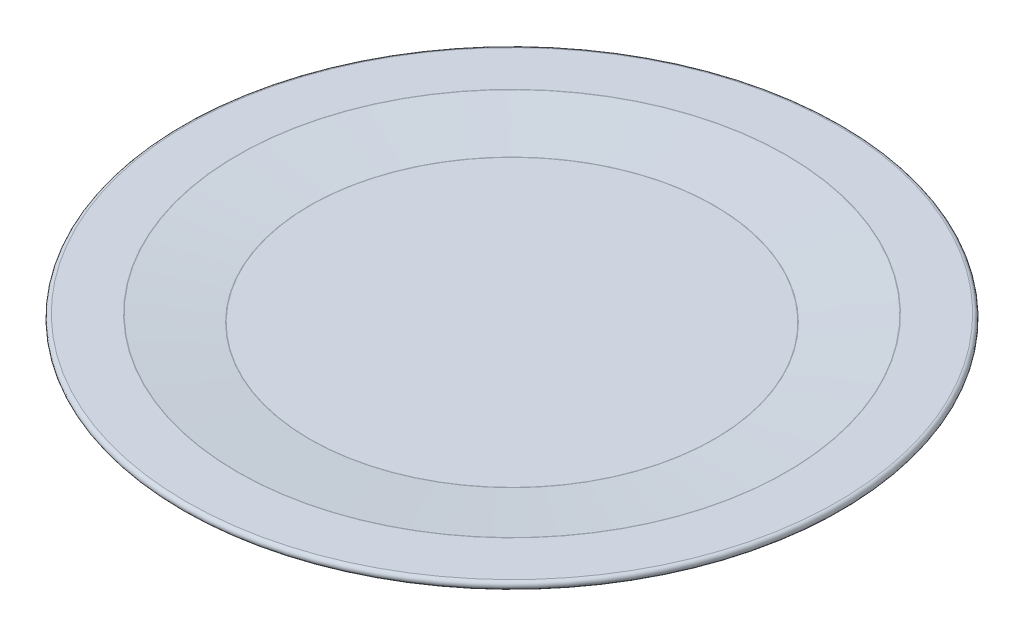
SolidWorks part; units mm, degrees
ref_plane "Front Plane" through (0, 0, 0) normal (0, 0, 1) x (1, 0, 0)
ref_plane "Top Plane" through (0, 0, 0) normal (0, 1, 0) x (1, 0, 0)
ref_plane "Right Plane" through (0, 0, 0) normal (1, 0, 0) x (0, 0, -1)
sketch "Sketch1" plane through (0, 0, 0) normal (0, 1, 0) x (1, 0, 0)
  circle A1 centre (0, 0) radius 203.2
extrude "Boss-Extrude1" add sketch "Sketch1" along normal blind 12.7 draft 64 draft outward yes
sketch "Sketch2" plane through (0, 12.7, 0) normal (0, 1, 0) x (1, 0, 0)
  circle A0 centre (0, 0) radius 183.8712
extrude "Cut-Extrude1" cut sketch "Sketch2" against normal blind 5.08 draft 84
fillet "Fillet1" radius 2.54 3 edges at (0, 7.62, 135.5383) (0, 12.7, 229.2389) (0, 12.7, 183.8712)
scale "Scale1" scale about centroid uniform scaling yes scale factor 0.582
